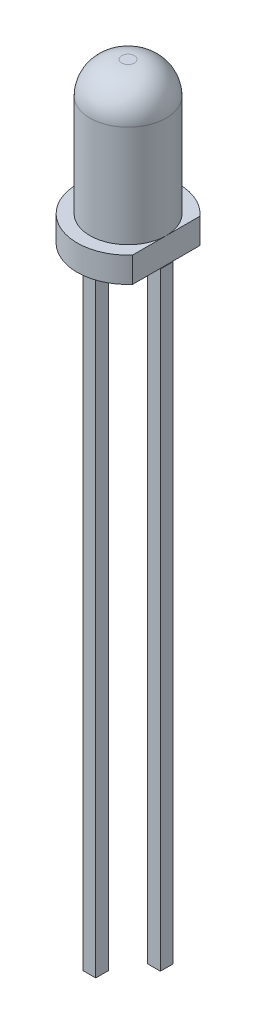
SolidWorks part; units mm, degrees
ref_plane "Alzado" through (0, 0, 0) normal (0, 0, 1) x (1, 0, 0)
ref_plane "Planta" through (0, 0, 0) normal (0, 1, 0) x (1, 0, 0)
ref_plane "Vista lateral" through (0, 0, 0) normal (1, 0, 0) x (0, 0, -1)
sketch "Croquis1" plane through (0, 0, 0) normal (0, 1, 0) x (1, 0, 0)
  circle A0 centre (0, 0) radius 2
  dimension "D1" = 4
extrude "Base" add sketch "Croquis1" along normal blind 1
sketch "Croquis2" plane through (0, 1, 0) normal (0, 1, 0) x (1, 0, 0)
  circle A0 centre (0, 0) radius 1.5
  dimension "D1" = 3
extrude "Cuerpo del LED" add sketch "Croquis2" along normal blind 5.25
sketch "Croquis3" plane through (0, 0, 0) normal (0, -1, 0) x (1, 0, 0)
  line L0 (-1.2701, 0) -> (0, 0) construction
  line L1 (0, 0) -> (1.2702, 0) construction
  line L2 (-1.5201, -0.25) -> (-1.0201, 0.25) construction
  line L3 (-1.5201, -0.25) -> (-1.0201, -0.25)
  line L4 (-1.5201, -0.25) -> (-1.5201, 0.25)
  line L5 (-1.5201, 0.25) -> (-1.0201, 0.25)
  line L6 (-1.0201, -0.25) -> (-1.0201, 0.25)
  line L7 (1.0202, -0.25) -> (1.5202, 0.25) construction
  line L8 (1.0202, -0.25) -> (1.5202, -0.25)
  line L9 (1.0202, -0.25) -> (1.0202, 0.25)
  line L10 (1.0202, 0.25) -> (1.5202, 0.25)
  line L11 (1.5202, -0.25) -> (1.5202, 0.25)
  dimension "D1" = 0.5
  dimension "D2" = 0.5
  dimension "D3" = 0.5
  dimension "D4" = 0.5
extrude "Pines" add sketch "Croquis3" along normal blind 25.4 from vertex at 0 starting at point (1.0202, 0, 0.25)
sketch "Croquis4" plane through (0, -25.4, 0) normal (0, -1, 0) x (1, 0, 0)
  line L4 (1.0202, 0.25) -> (1.0202, -0.25)
  line L5 (1.0202, -0.25) -> (1.5202, -0.25)
  line L6 (1.5202, -0.25) -> (1.5202, 0.25)
  line L7 (1.5202, 0.25) -> (1.0202, 0.25)
  line L8 (1.0202, 0.25) -> (1.0202, -0.25)
  line L9 (1.0202, -0.25) -> (1.5202, -0.25)
  line L10 (1.5202, -0.25) -> (1.5202, 0.25)
  line L11 (1.5202, 0.25) -> (1.0202, 0.25)
  dimension "D1" = 0
extrude "Corte a Catodo" cut sketch "Croquis4" against normal blind 1.5
sketch "Croquis6" plane through (0, 1, 0) normal (0, 1, 0) x (1, 0, 0)
  line L0 (2, 0) -> (1.5, 0) construction
  line L1 (1.5, 2.7304) -> (1.5, -1.7696)
  line L2 (1.5, -1.7696) -> (2.5, -1.7696)
  line L3 (2.5, -1.7696) -> (2.5, 2.7304)
  line L4 (2.5, 2.7304) -> (1.5, 2.7304)
  circle A0 centre (0, 0) radius 2 construction
  circle A1 centre (0, 0) radius 1.5 construction
  dimension "D1" = 4.5
  dimension "D2" = 1
extrude "Ranura" cut sketch "Croquis6" against normal up to surface (1 mm away) up to face at (-1.2701, 0, 0)
fillet "Punta del Led" radius 1.25 1 edges at (0, 6.25, 1.5)
